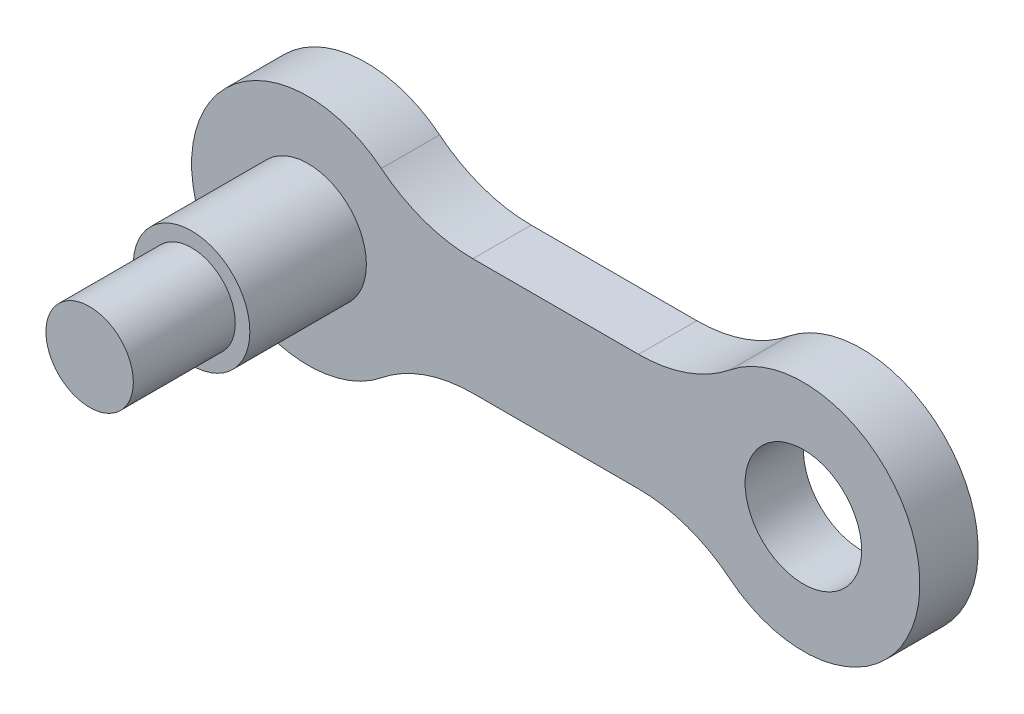
SolidWorks part; units mm, degrees
ref_plane "Front Plane" through (0, 0, 0) normal (0, 0, 1) x (1, 0, 0)
ref_plane "Top Plane" through (0, 0, 0) normal (0, 1, 0) x (1, 0, 0)
ref_plane "Right Plane" through (0, 0, 0) normal (1, 0, 0) x (0, 0, -1)
sketch "Sketch1" plane through (0, 0, 0) normal (0, 0, 1) x (1, 0, 0)
  line L2 (5.6569, 2) -> (11.3431, 2)
  line L4 (5.6569, -2) -> (11.3431, -2)
  arc A1 (14.4858, -3.1111) -> (14.4858, 3.1111) centre (17, 0) ccw
  arc A2 (2.5142, 3.1111) -> (2.5142, -3.1111) centre (0, 0) ccw
  arc A3 (2.5142, 3.1111) -> (5.6569, 2) centre (5.6569, 7) ccw
  arc A4 (14.4858, 3.1111) -> (11.3431, 2) centre (11.3431, 7) cw
  arc A5 (14.4858, -3.1111) -> (11.3431, -2) centre (11.3431, -7) ccw
  arc A6 (5.6569, -2) -> (2.5142, -3.1111) centre (5.6569, -7) ccw
  circle A7 centre (0, 0) radius 2
  circle A8 centre (17, 0) radius 2
  circle A9 centre (0, 0) radius 2
  circle A10 centre (0, 0) radius 1.5
  dimension "D1" = 5
  dimension "D2" = 5
extrude "Boss-Extrude1" add sketch "Sketch1" along normal blind 2 contours A6 L4 A5 A1 A4 L2 A3 A2 A8 A7
sketch "Sketch2" plane through (0, 0, 2) normal (0, 0, 1) x (1, 0, 0)
  circle A0 centre (0, 0) radius 2
  circle A1 centre (0, 0) radius 1.5
extrude "Boss-Extrude2" add sketch "Sketch2" along normal blind 4 separate body
sketch "Sketch3" plane through (0, 0, 6) normal (0, 0, 1) x (1, 0, 0)
  circle A1 centre (0, 0) radius 1.5
extrude "Boss-Extrude3" add sketch "Sketch3" along normal blind 3.5 separate body
